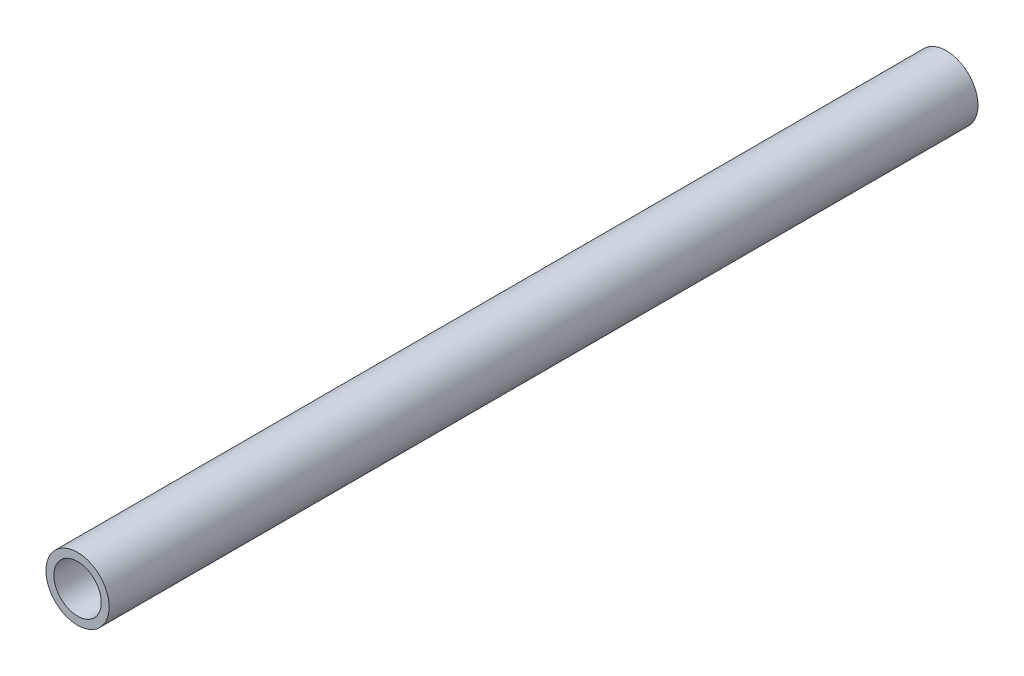
SolidWorks part; units mm, degrees
material "Thornel Mat VMA"
ref_plane "Front Plane" through (0, 0, 0) normal (0, 0, 1) x (1, 0, 0)
ref_plane "Top Plane" through (0, 0, 0) normal (0, 1, 0) x (1, 0, 0)
ref_plane "Right Plane" through (0, 0, 0) normal (1, 0, 0) x (0, 0, -1)
sketch "Sketch1" plane through (0, 0, 0) normal (0, 0, 1) x (1, 0, 0)
  line L5 (-5, 5) -> (5, -5) construction
  line L6 (-5, -5) -> (5, 5) construction
  circle A0 centre (0, 0) radius 4
  circle A1 centre (0, 0) radius 3
  point P0 (0, 0)
  dimension "D1" = 8
  dimension "D2" = 10
  dimension "D3" = 1
extrude "Boss-Extrude1" add sketch "Sketch1" along normal blind 110
